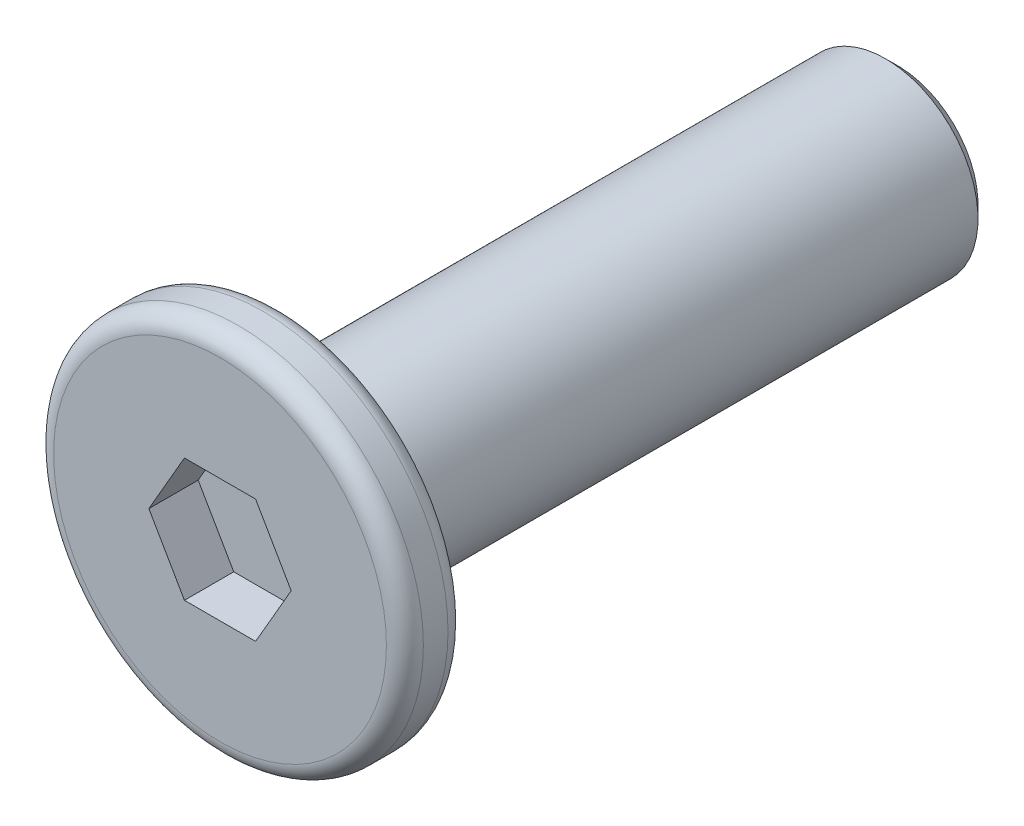
SolidWorks part; units mm, degrees
ref_plane "前视基准面" through (0, 0, 0) normal (0, 0, 1) x (1, 0, 0)
ref_plane "上视基准面" through (0, 0, 0) normal (0, 1, 0) x (1, 0, 0)
ref_plane "右视基准面" through (0, 0, 0) normal (1, 0, 0) x (0, 0, -1)
sketch "草图1" plane through (0, 0, 0) normal (0, 0, 1) x (1, 0, 0)
  circle A0 centre (0, 0) radius 3
  dimension "D1" = 6
extrude "凸台-拉伸1" add sketch "草图1" along normal mid plane 1
sketch "草图2" plane through (0, 0, -0.5) normal (0, 0, -1) x (-1, 0, 0)
  circle A0 centre (0, 0) radius 1.5
  dimension "D1" = 3
extrude "凸台-拉伸2" add sketch "草图2" along normal blind 10
chamfer "倒角1" distance 0.2 angle 45 1 edges at (-1.5, 0, -10.5)
sketch "草图3" plane through (0, 0, 0.5) normal (0, 0, 1) x (1, 0, 0)
  line L1 (1.1547, 0) -> (0.5774, 1)
  line L2 (0.5774, 1) -> (-0.5774, 1)
  line L3 (-0.5774, 1) -> (-1.1547, 0)
  line L4 (-1.1547, 0) -> (-0.5774, -1)
  line L5 (-0.5774, -1) -> (0.5774, -1)
  line L6 (0.5774, -1) -> (1.1547, 0)
  circle A0 centre (0, 0) radius 1 construction
  dimension "D1" = 2
extrude "切除-拉伸1" cut sketch "草图3" against normal blind 0.8
fillet "圆角2" radius 0.3 2 edges at (3, 0, -0.5) (3, 0, 0.5)
